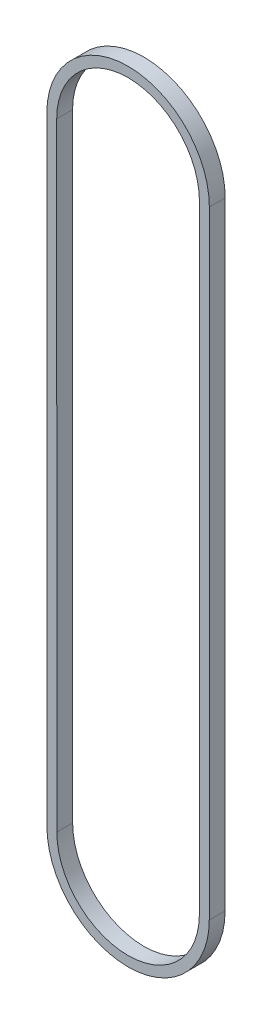
SolidWorks part; units mm, degrees
material "BUTYL"
ref_plane "Front Plane" through (0, 0, 0) normal (0, 0, 1) x (1, 0, 0)
ref_plane "Top Plane" through (0, 0, 0) normal (0, 1, 0) x (1, 0, 0)
ref_plane "Right Plane" through (0, 0, 0) normal (1, 0, 0) x (0, 0, -1)
sketch "Sketch1" plane through (0, 0, 0) normal (0, 0, 1) x (1, 0, 0)
  line L0 (-26.3106, 125.8978) -> (-26.2852, -32.5855)
  line L1 (-5.4572, -35.3202) -> (-5.4572, -32.5822) construction
  line L2 (-5.4572, -32.5822) -> (-5.4572, -13.1122) construction
  line L3 (15.3962, 125.8978) -> (15.3708, -32.5855)
  line L4 (-23.7706, 125.8982) -> (-23.7452, -32.5851)
  line L5 (12.8562, 125.8982) -> (12.8308, -32.5851)
  arc A0 (-26.2852, -32.5855) -> (15.3708, -32.5855) centre (-5.4572, -32.5822) ccw
  arc A1 (15.3962, 125.8978) -> (-26.3106, 125.8978) centre (-5.4572, 125.9011) ccw
  arc A2 (-23.7452, -32.5851) -> (12.8308, -32.5851) centre (-5.4572, -32.5822) ccw
  arc A3 (12.8562, 125.8982) -> (-23.7706, 125.8982) centre (-5.4572, 125.9011) ccw
  dimension "D1" = 41.7068
  dimension "D2" = 41.656
  dimension "D4" = 158.4833
  dimension "D3" = 2.54
extrude "Boss-Extrude1" add sketch "Sketch1" along normal blind 4.064
